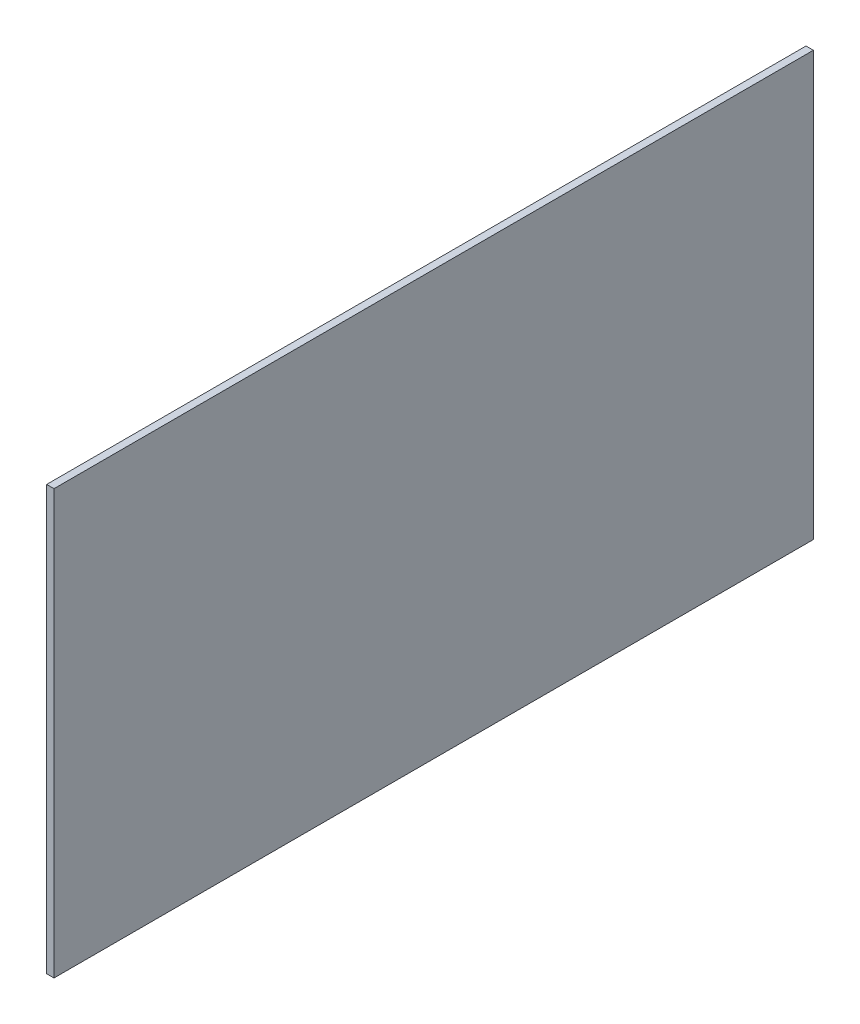
SolidWorks part; units mm, degrees
ref_plane "Front Plane" through (0, 0, 0) normal (0, 0, 1) x (1, 0, 0)
ref_plane "Top Plane" through (0, 0, 0) normal (0, 1, 0) x (1, 0, 0)
ref_plane "Right Plane" through (0, 0, 0) normal (1, 0, 0) x (0, 0, -1)
sketch "Sketch1" plane through (0, 0, 0) normal (1, 0, 0) x (0, 0, -1)
  line L1 (-246.0625, -137.3187) -> (246.0625, -137.3187)
  line L2 (-246.0625, -137.3187) -> (-246.0625, 137.3188)
  line L3 (-246.0625, 137.3188) -> (246.0625, 137.3188)
  line L4 (246.0625, -137.3187) -> (246.0625, 137.3188)
  line L5 (-246.0625, -137.3187) -> (246.0625, 137.3188) construction
  line L6 (-246.0625, 137.3188) -> (246.0625, -137.3187) construction
  point P0 (0, 0)
  dimension "D1" = 274.6375
  dimension "D2" = 492.125
extrude "Boss-Extrude1" add sketch "Sketch1" along normal blind 4.7625
